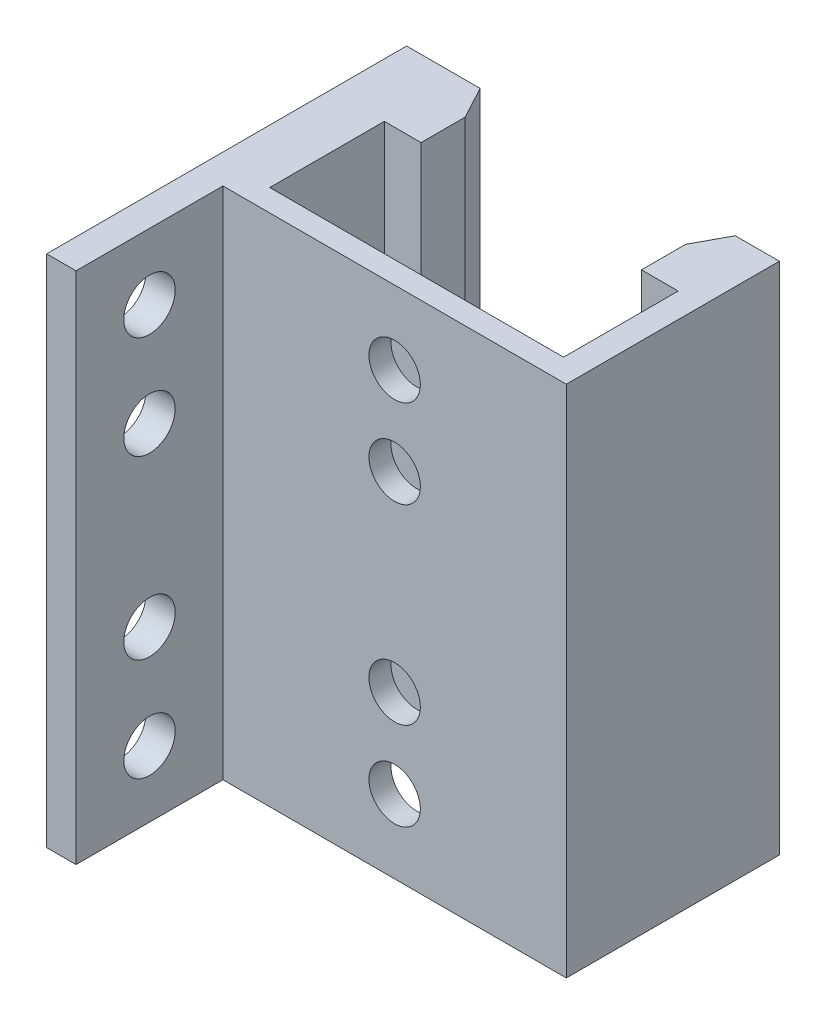
SolidWorks part; units mm, degrees
ref_plane "Front Plane" through (0, 0, 0) normal (0, 0, 1) x (1, 0, 0)
ref_plane "Top Plane" through (0, 0, 0) normal (0, 1, 0) x (1, 0, 0)
ref_plane "Right Plane" through (0, 0, 0) normal (1, 0, 0) x (0, 0, -1)
sketch "Sketch1" plane through (0, 0, 0) normal (0, 1, 0) x (1, 0, 0)
  line L0 (-11.6838, 0) -> (11.6838, 0)
  line L1 (11.6838, 0) -> (11.6838, 14.5)
  line L2 (11.6838, 14.5) -> (8.6838, 14.5)
  line L3 (8.6838, 14.5) -> (7.5, 12.3)
  line L4 (7.5, 12.3) -> (7.5, 9.3)
  line L5 (7.5, 9.3) -> (10, 9.3)
  line L6 (10, 9.3) -> (10, 1.5)
  line L7 (10, 1.5) -> (-10, 1.5)
  line L8 (0, 1.5) -> (0, 0)
  line L9 (-10, 9.3) -> (-10, 1.5)
  line L10 (-7.5, 9.3) -> (-10, 9.3)
  line L11 (-7.5, 12.3) -> (-7.5, 9.3)
  line L12 (-8.6838, 14.5) -> (-7.5, 12.3)
  line L13 (-11.6838, 14.5) -> (-8.6838, 14.5)
  line L14 (-11.6838, 0) -> (-11.6838, 14.5)
  dimension "D1" = 10
  dimension "D2" = 7.8
  dimension "D3" = 2.5
  dimension "D4" = 3
  dimension "D5" = 2.2
  dimension "D6" = 3
  dimension "D7" = 14.5
extrude "Boss-Extrude1" add sketch "Sketch1" along normal blind 35 contours L7 L9 L10 L11 L12 L13 L14 L0 L1 L2 L3 L4 L5 L6
sketch "Sketch2" plane through (0, 0, 0) normal (0, 0, 1) x (1, 0, 0)
  line L0 (-11.6838, 17.5) -> (11.6838, 17.5) construction
  line L1 (-11.6838, 35) -> (-11.6838, 0) construction
  line L2 (11.6838, 35) -> (11.6838, 0) construction
  line L3 (0, 35) -> (0, 0) construction
  line L4 (-11.6838, 35) -> (11.6838, 35) construction
  circle A0 centre (0, 5) radius 1.75
  circle A1 centre (0, 24) radius 1.75
  circle A2 centre (0, 11) radius 1.75
  circle A3 centre (0, 30) radius 1.75
  dimension "D1" = 19
  dimension "D2" = 19
  dimension "D3" = 3.5
  dimension "D4" = 6.5
  dimension "D5" = 6.5
extrude "Cut-Extrude1" cut sketch "Sketch2" against normal blind 10 contours A1 | A0 | A3 | A2
sketch "Optical Mount" plane through (-11.6838, 0, 0) normal (-1, 0, 0) x (0, 0, 1)
  line L0 (0, 35) -> (-14.5, 35) construction
  line L1 (0, 0) -> (10, 0)
  line L3 (0, 35) -> (10, 35)
  line L4 (10, 0) -> (10, 35)
  line L6 (-14.5, 0) -> (0, 0)
  line L7 (-14.5, 0) -> (-14.5, 35)
  line L8 (-14.5, 35) -> (0, 35)
  dimension "D1" = 10
  dimension "D2" = 14.5
extrude "Mounting Wing" add sketch "Optical Mount" along normal blind 2
sketch "Sketch5" plane through (-11.6838, 0, 0) normal (1, 0, 0) x (0, 0, -1)
  line L0 (-5, 35) -> (-5, 0) construction
  line L3 (-10, 17.5) -> (0, 17.5) construction
  line L4 (-10, 0) -> (-10, 35) construction
  line L5 (0, 35) -> (0, 0) construction
  line L6 (-10, 35) -> (0, 35) construction
  line L7 (0, 0) -> (-10, 0) construction
  circle A0 centre (-5, 4.5) radius 1.75
  circle A1 centre (-5, 11.5) radius 1.75
  circle A2 centre (-5, 23.5) radius 1.75
  circle A3 centre (-5, 30.5) radius 1.75
  dimension "D1" = 3.5
  dimension "D2" = 19
  dimension "D3" = 19
  dimension "D4" = 6
  dimension "D5" = 6
extrude "Cut-Extrude2" cut sketch "Sketch5" against normal blind 3.5
